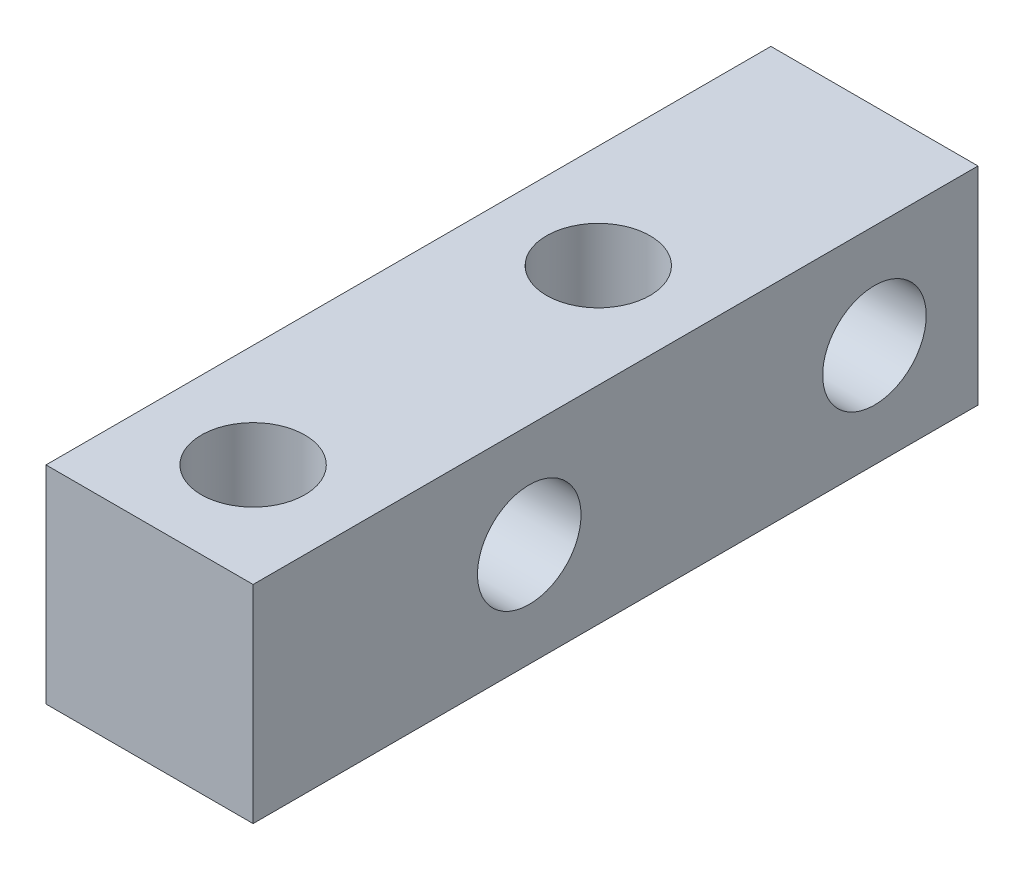
SolidWorks part; units mm, degrees
material "6061 合金"
ref_plane "前视基准面" through (0, 0, 0) normal (0, 0, 1) x (1, 0, 0)
ref_plane "上视基准面" through (0, 0, 0) normal (0, 1, 0) x (1, 0, 0)
ref_plane "右视基准面" through (0, 0, 0) normal (1, 0, 0) x (0, 0, -1)
other "Configuration Table"
sketch "草图1" plane through (0, 0, 0) normal (0, 1, 0) x (1, 0, 0)
  line L1 (-3, -3) -> (3, -3)
  line L2 (-3, -3) -> (-3, 18)
  line L3 (-3, 18) -> (3, 18)
  line L4 (3, -3) -> (3, 18)
  circle A0 centre (0, 0) radius 1.5
  circle A1 centre (0, 10) radius 1.5
  point P5 (0, -3)
  dimension "D1" = 10
  dimension "D2" = 3
  dimension "D3" = 21
  dimension "D4" = 3
  dimension "D5" = 6
extrude "凸台-拉伸1" add sketch "草图1" along normal blind 6
sketch "草图2" plane through (3, 0, 0) normal (1, 0, 0) x (0, 0, -1)
  line L1 (18, 6) -> (18, 0) construction
  circle A0 centre (5, 3) radius 1.5
  circle A1 centre (15, 3) radius 1.5
  dimension "D4" = 3
  dimension "D1" = 3
  dimension "D2" = 10
  dimension "D3" = 3
extrude "切除-拉伸1" cut sketch "草图2" against normal blind 6
